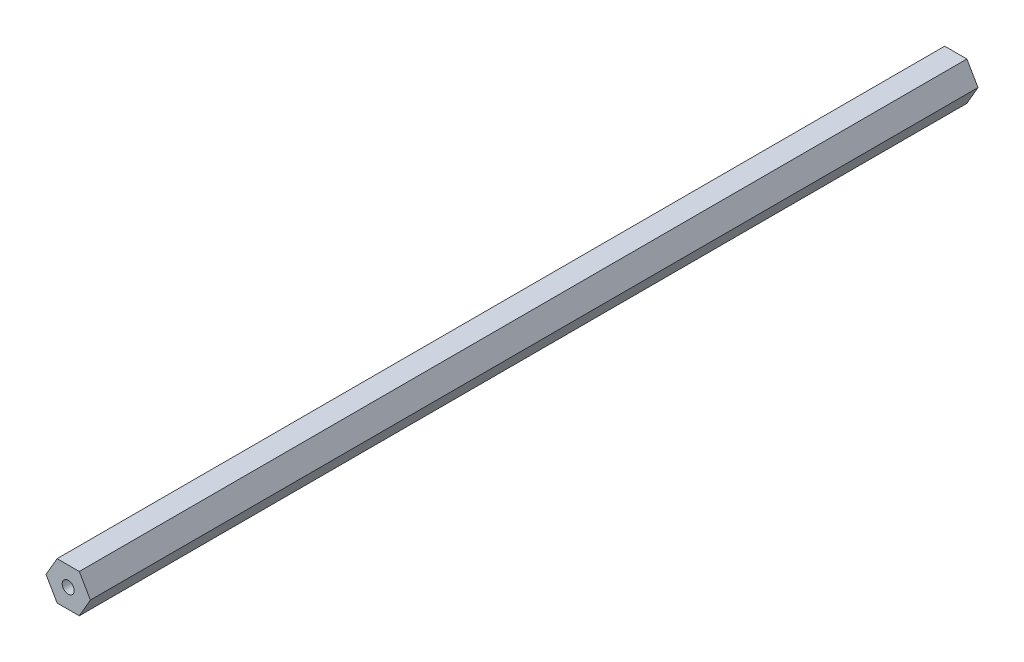
SolidWorks part; units mm, degrees
material "1060 Alloy"
ref_plane "Front Plane" through (0, 0, 0) normal (0, 0, 1) x (1, 0, 0)
ref_plane "Top Plane" through (0, 0, 0) normal (0, 1, 0) x (1, 0, 0)
ref_plane "Right Plane" through (0, 0, 0) normal (1, 0, 0) x (0, 0, -1)
sketch "Sketch1" plane through (0, 0, 0) normal (0, 0, 1) x (1, 0, 0)
  line L1 (6.35, 0) -> (3.175, 5.4993)
  line L2 (3.175, 5.4993) -> (-3.175, 5.4993)
  line L3 (-3.175, 5.4993) -> (-6.35, 0)
  line L4 (-6.35, 0) -> (-3.175, -5.4993)
  line L5 (-3.175, -5.4993) -> (3.175, -5.4993)
  line L6 (3.175, -5.4993) -> (6.35, 0)
  circle A0 centre (0, 0) radius 5.4993 construction
  circle A1 centre (0, 0) radius 1.7145
  dimension "D2" = 3.429
  dimension "D1" = 12.7
extrude "Boss-Extrude1" add sketch "Sketch1" along normal mid plane 254
equation "\"length\" = 10"
equation "\"D1@Boss-Extrude1\"=\"length\""
